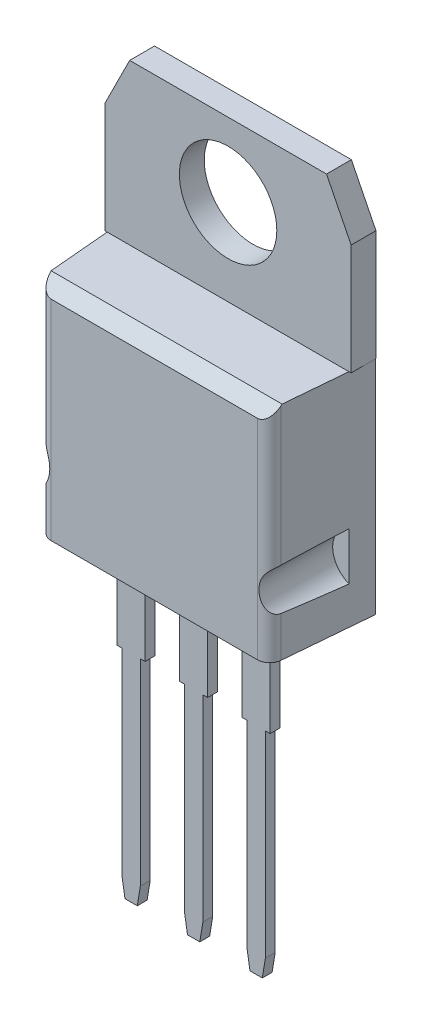
SolidWorks part; units mm, degrees
ref_plane "Front Plane" through (0, 0, 0) normal (0, 0, 1) x (1, 0, 0)
ref_plane "Top Plane" through (0, 0, 0) normal (0, 1, 0) x (1, 0, 0)
ref_plane "Right Plane" through (0, 0, 0) normal (1, 0, 0) x (0, 0, -1)
sketch "Sketch2" plane through (0, 0, 0) normal (0, 0, 1) x (1, 0, 0)
  line L1 (-5, -4.5) -> (5, -4.5)
  line L2 (-5, -4.5) -> (-5, 4.5)
  line L3 (-5, 4.5) -> (5, 4.5)
  line L4 (5, -4.5) -> (5, 4.5)
  line L5 (-5, -4.5) -> (5, 4.5) construction
  line L6 (-5, 4.5) -> (5, -4.5) construction
  point P0 (0, 0)
  dimension "D1" = 10
  dimension "D2" = 9
extrude "Boss-Extrude1" add sketch "Sketch2" along normal blind 4
chamfer "Chamfer1" distance 0.5 angle 45 1 edges at (0, 4.5, 4)
sketch "Sketch6" plane through (0, 0, 4) normal (0, 0, 1) x (1, 0, 0)
  line L0 (5, -4.5) -> (5, 4) construction
  line L1 (-5, -4.5) -> (5, -4.5) construction
  line L2 (5, -1) -> (5, -3)
  arc A0 (5, -3) -> (5, -1) centre (5.2917, -2) cw
  point P7 (4.25, -2)
  dimension "D1" = 1.5
  dimension "D2" = 2
  dimension "D3" = 0.75
extrude "Cut-Extrude1" cut sketch "Sketch6" against normal blind 3 contours A0 L2
mirror "Mirror1" about plane through (0, 0, 0) normal (1, 0, 0) of "Cut-Extrude1"
ref_plane "Plane1" through (0, 0, 2) normal (0, 0, 1) x (1, 0, 0)
sketch "Sketch7" plane through (0, 0, 2) normal (0, 0, 1) x (1, 0, 0)
  line L0 (-0.57, -4.5) -> (-0.57, -8.44)
  line L1 (-5, -4.5) -> (5, -4.5) construction
  line L2 (-0.57, -8.44) -> (-0.375, -8.44)
  line L3 (-0.375, -8.44) -> (-0.375, -16.44)
  line L4 (-0.375, -16.44) -> (-0.25, -17.2)
  line L5 (-0.25, -17.2) -> (0.25, -17.2)
  line L6 (0.25, -17.2) -> (0.375, -16.44)
  line L7 (0.375, -16.44) -> (0.375, -8.44)
  line L8 (0.375, -8.44) -> (0.57, -8.44)
  line L9 (0.57, -8.44) -> (0.57, -4.5)
  line L10 (0.57, -4.5) -> (-0.57, -4.5)
  point P5 (0, -17.2)
  point P13 (-0.2483, -17.2)
  point P14 (-0.2483, -17.2)
  dimension "D1" = 3.94
  dimension "D2" = 8.76
  dimension "D3" = 1.14
  dimension "D4" = 0.75
  dimension "D5" = 8
  dimension "D6" = 0.5
  dimension "D7" = 0.57
extrude "Boss-Extrude2" add sketch "Sketch7" along normal blind 0.4 contours L0 L2 L3 L4 L5 L6 L7 L8 L9 L10
pattern_linear "LPattern1" count 2 spacing 2.54 along (-1, 0, 0) of "Boss-Extrude2"
pattern_linear "LPattern2" count 2 spacing 2.54 along (1, 0, 0) of "Boss-Extrude2"
draft "Draft2" type of draft neutral plane draft angle 5 faces to draft 2 face at (5, -0.4444, 2.3889) face at (-5, -0.4444, 2.3889) neutral plane through (0, 0, 0) neutral plane normal (0, 0, -1) reverse direction yes parameters "D1"=5
sketch "Sketch8" plane through (0, 0, 0) normal (0, 0, -1) x (-1, 0, 0)
  line L0 (-5, 9) -> (-4, 11)
  line L1 (-5, 4.5) -> (5, 4.5)
  line L2 (-5, 4.5) -> (-5, 9)
  line L3 (-4, 11) -> (4, 11)
  line L4 (5, 4.5) -> (5, 9)
  line L5 (4, 11) -> (5, 9)
  circle A0 centre (0, 8) radius 1.98
  point P1 (5, 11)
  point P2 (-5, 11)
  point P11 (0, 0)
  dimension "D7" = 3.96
  dimension "D1" = 6.5
  dimension "D2" = 10
  dimension "D3" = 2
  dimension "D4" = 1
  dimension "D5" = 1
  dimension "D6" = 2
  dimension "D8" = 3
extrude "Boss-Extrude3" add sketch "Sketch8" against normal blind 1 and the other way blind 0.01
fillet "Fillet1" radius 0.5 2 edges at (-4.65, 1.4103, 4) (4.65, 1.4103, 4)
